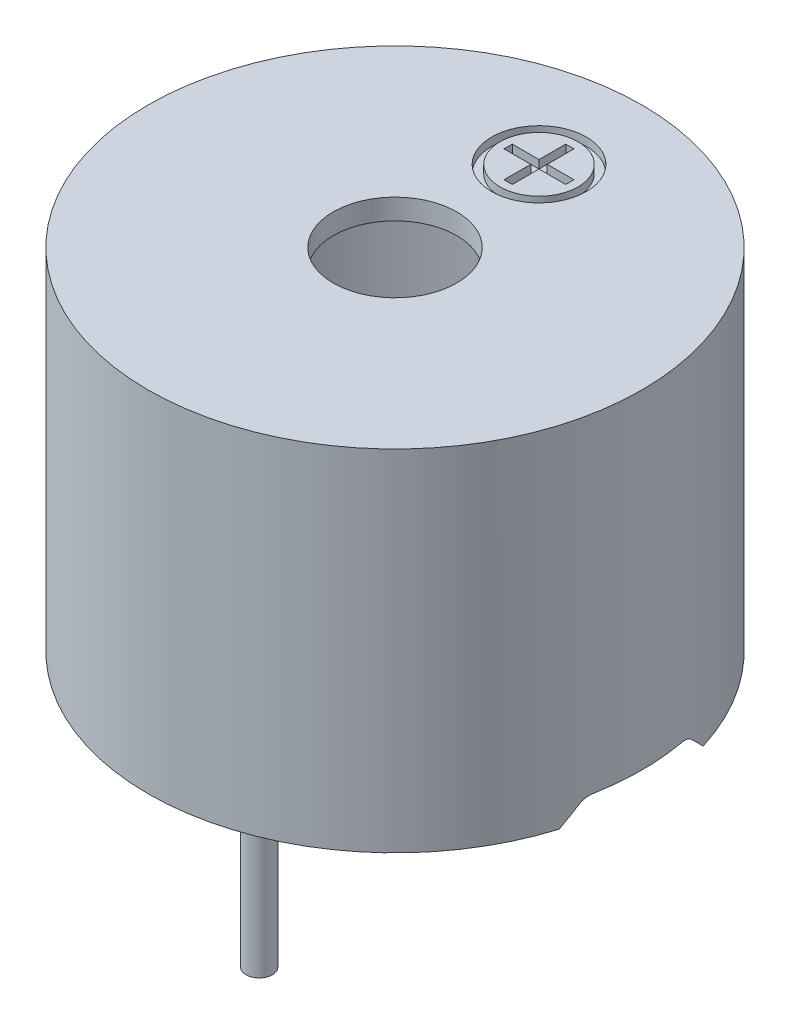
SolidWorks part; units mm, degrees
other "Body"
other "Board"
other "Quartz"
other "Plate" parameters "D1"=43.5962, "D2"=1.2006
ref_plane "Front Plane" through (0, 0, 0) normal (0, 0, 1) x (1, 0, 0)
ref_plane "Top Plane" through (0, 0, 0) normal (0, 1, 0) x (1, 0, 0)
ref_plane "Right Plane" through (0, 0, 0) normal (1, 0, 0) x (0, 0, -1)
sketch "Sketch1" plane through (0, 0, 0) normal (0, 1, 0) x (1, 0, 0)
  circle A0 centre (0, 0) radius 6
  dimension "D1" = 12
extrude "Boss-Extrude1" add sketch "Sketch1" along normal blind 8.5
sketch "Sketch2" plane through (0, 0, 0) normal (0, -1, 0) x (-1, 0, 0)
  circle A0 centre (0, 0) radius 5.5
  circle A1 centre (0, 0) radius 6 construction
  dimension "D1" = 0.5
extrude "Cut-Extrude1" cut sketch "Sketch2" against normal blind 8
sketch "Sketch3" plane through (0, 8.5, 0) normal (0, 1, 0) x (1, 0, 0)
  circle A0 centre (0, 0) radius 1.5
  dimension "D1" = 3
extrude "Cut-Extrude2" cut sketch "Sketch3" against normal up to next
sketch "Sketch4" plane through (0, 8.5, 0) normal (0, 1, 0) x (1, 0, 0)
  line L0 (0.75, 3.5) -> (-0.75, 3.5)
  line L1 (0, 2.75) -> (0, 4.25)
  circle A0 centre (0, 3.5) radius 1.05
  circle A1 centre (0, 3.5) radius 0.75 construction
  point P2 (0, 3.5)
  point P6 (0, 3.5)
  dimension "D3" = 0.3
  dimension "D1" = 3.5
  dimension "D2" = 1.5
extrude "Cut-Extrude-Thin1" cut sketch "Sketch4" against normal blind 0.2 thin thin type mid plane wall 0.2
ref_plane "Plane1" through (6, 0, 0) normal (1, 0, 0) x (0, 0, -1)
sketch "Sketch5" plane through (6, 0, 0) normal (1, 0, 0) x (0, 0, -1)
  line L0 (-1.0843, 0.5) -> (1.0843, 0.5)
  line L1 (1.3672, 0.3828) -> (1.75, 0)
  line L2 (-6, 0) -> (6, 0) construction
  line L3 (1.75, 0) -> (-1.75, 0)
  line L4 (-1.75, 0) -> (-1.3672, 0.3828)
  arc A0 (1.3672, 0.3828) -> (1.0843, 0.5) centre (1.0843, 0.1) ccw
  arc A1 (-1.0843, 0.5) -> (-1.3672, 0.3828) centre (-1.0843, 0.1) ccw
  point P5 (0, 0.5)
  point P8 (0, 0)
  point P13 (1.25, 0.5)
  point P16 (-1.25, 0.5)
  dimension "D4" = 0.4
  dimension "D1" = 45
  dimension "D2" = 0.5
  dimension "D3" = 2.5
extrude "Cut-Extrude3" cut sketch "Sketch5" against normal through all
ref_plane "Plane2" through (0, 1, 0) normal (0, 1, 0) x (1, 0, 0)
sketch "Sketch6" plane through (0, 1, 0) normal (0, 1, 0) x (1, 0, 0)
  line L0 (0, 3.3) -> (0, -3.3) construction
  circle A0 centre (0, 0) radius 5.5
  circle A1 centre (0, 0) radius 5.5 construction
  circle A2 centre (0, 3.3) radius 0.32
  circle A3 centre (0, -3.3) radius 0.32
  point P9 (0, 0)
  dimension "D2" = 0.64
  dimension "D1" = 6.6
extrude "Board extrude" add sketch "Sketch6" along normal blind 0.2 separate body
sketch "Sketch7" plane through (0, 1.2, 0) normal (0, 1, 0) x (1, 0, 0)
  circle A0 centre (0, 3.3) radius 0.32
  circle A1 centre (0, -3.3) radius 0.32
  circle A2 centre (0, 3.3) radius 0.32 construction
  circle A3 centre (0, -3.3) radius 0.32 construction
extrude "Pins" add sketch "Sketch7" against normal offset from surface (6.2 mm away) 5 separate body up to face at (0, 0, -3.75) offset beyond the face yes
sketch "Sketch8" plane through (0, 1.2, 0) normal (0, 1, 0) x (1, 0, 0)
  circle A0 centre (0, 0) radius 2.5
  dimension "D1" = 5
extrude "Quartz extrude" add sketch "Sketch8" along normal blind 1 separate body
sketch "Sketch9" plane through (0, 2.2, 0) normal (0, 1, 0) x (1, 0, 0)
  circle A0 centre (0, 0) radius 5
  circle A1 centre (0, 0) radius 5.5 construction
  dimension "D1" = 0.5
extrude "Plate extrude" add sketch "Sketch9" along normal blind 0.1 separate body
equation "\"D\"= 12"
equation "\"H\"= 8.5"
equation "\"P\"= 6.6"
equation "\"Pin size\"= .64"
equation "\"D1@Sketch1\"=\"D\""
equation "\"D1@Boss-Extrude1\"=\"H\""
equation "\"D1@Cut-Extrude1\"=\"H\"-0.5"
equation "\"D1@Sketch6\"=\"P\""
equation "\"D2@Sketch6\"=\"Pin size\""
equation "\"Pin length\"= 5"
equation "\"D1@Pins\" = \"Pin length\""
